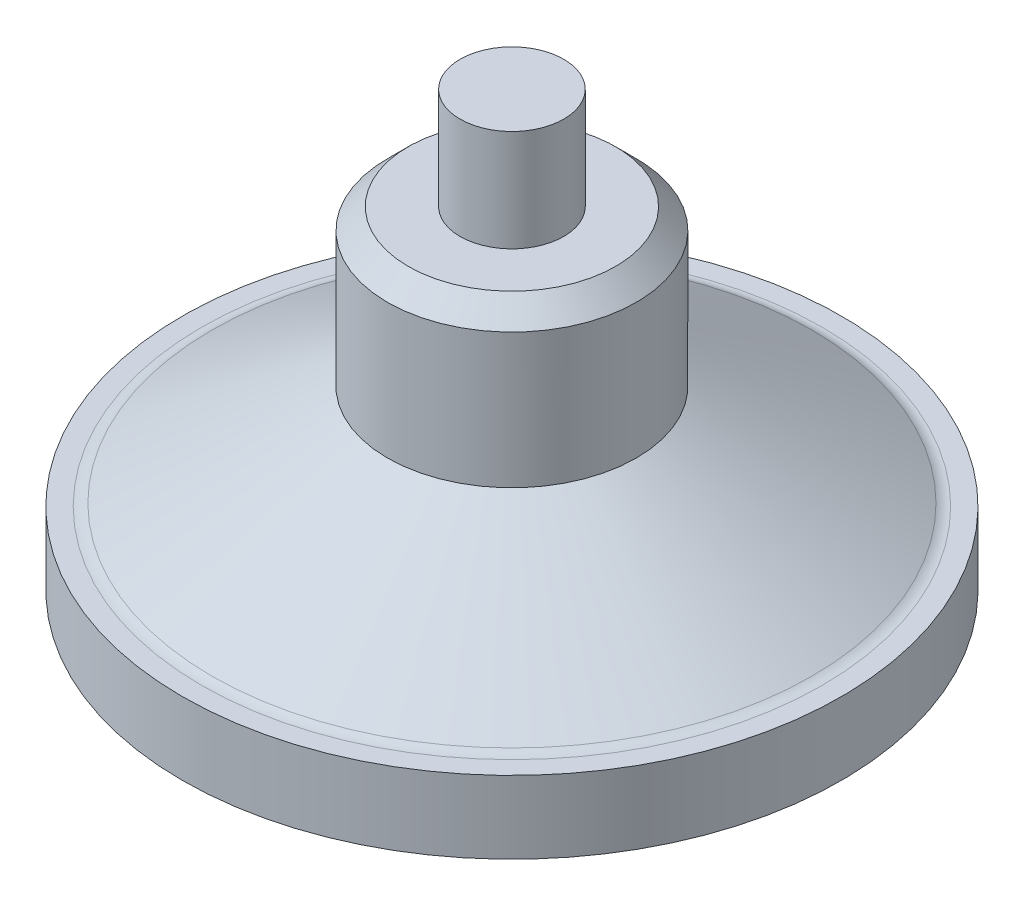
SolidWorks part; units mm, degrees
ref_plane "Front Plane" through (0, 0, 0) normal (0, 0, 1) x (1, 0, 0)
ref_plane "Top Plane" through (0, 0, 0) normal (0, 1, 0) x (1, 0, 0)
ref_plane "Right Plane" through (0, 0, 0) normal (1, 0, 0) x (0, 0, -1)
sketch "Sketch1" plane through (0, 0, 0) normal (0, 0, 1) x (1, 0, 0)
  line L0 (0, 31.9758) -> (0, -31.9758) construction
  line L1 (2.5, 10.999) -> (2.5, 15.899)
  line L2 (5.0622, 0) -> (13.75, -5.0159)
  line L3 (6, 3.5) -> (14.6878, -1.5159)
  line L4 (15.8878, -5.0159) -> (13.75, -5.0159)
  line L5 (2.5, 15.899) -> (0, 15.899)
  line L6 (5.0622, 0) -> (0, 0)
  line L7 (6, 3.5) -> (6, 10.999)
  line L8 (2.5, 10.999) -> (6, 10.999)
  line L9 (0, 0) -> (0, 3.5)
  line L10 (0, 15.899) -> (0, 3.5)
  line L11 (14.6878, -1.5159) -> (15.8878, -1.5159)
  line L12 (15.8878, -1.5159) -> (15.8878, -5.0159)
  point P4 (0, 0)
  dimension "D6" = 3.5
  dimension "D1" = 5
  dimension "D2" = 3.5
  dimension "D3" = 3.5
  dimension "D4" = 150
  dimension "D5" = 27.5
  dimension "D7" = 10.999
  dimension "D8" = 3.5
  dimension "D9" = 1.2
  dimension "D10" = 4.9
revolve "Revolve1" add sketch "Sketch1" angle 360 about L0
fillet "Fillet1" radius 3 1 edges at (0, -5.0159, 13.75)
chamfer "Chamfer1" distance 1 angle 45 1 edges at (0, 10.999, 6)
fillet "Fillet2" radius 1 1 edges at (0, -1.5159, 14.6878)
